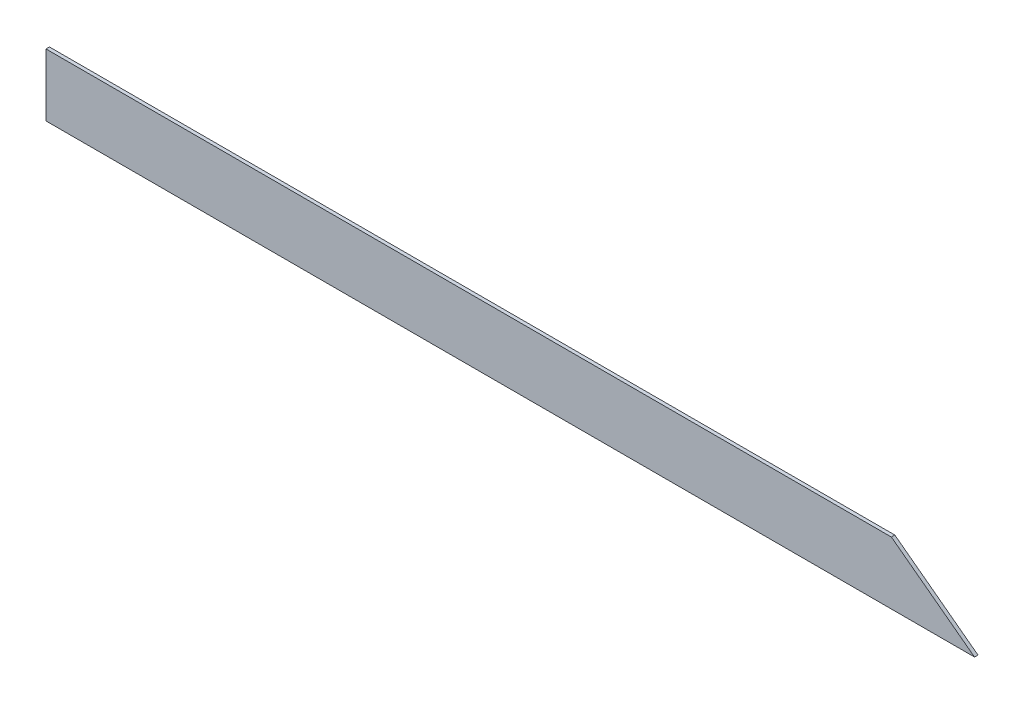
SolidWorks part; units mm, degrees
material "Magnesium Alloy"
ref_plane "Front Plane" through (0, 0, 0) normal (0, 0, 1) x (1, 0, 0)
ref_plane "Top Plane" through (0, 0, 0) normal (0, 1, 0) x (1, 0, 0)
ref_plane "Right Plane" through (0, 0, 0) normal (1, 0, 0) x (0, 0, -1)
sketch "Sketch2" plane through (0, 0, 0) normal (0, 0, 1) x (1, 0, 0)
  line L0 (0, 0) -> (425.45, 0)
  line L2 (387.35, 28.575) -> (0, 28.575)
  line L3 (0, 28.575) -> (0, 0)
  line L4 (425.45, 0) -> (387.35, 28.575)
  dimension "D1" = 28.575
  dimension "D2" = 425.45
  dimension "D3" = 38.1
extrude "Boss-Extrude1" add sketch "Sketch2" along normal blind 1.5875
